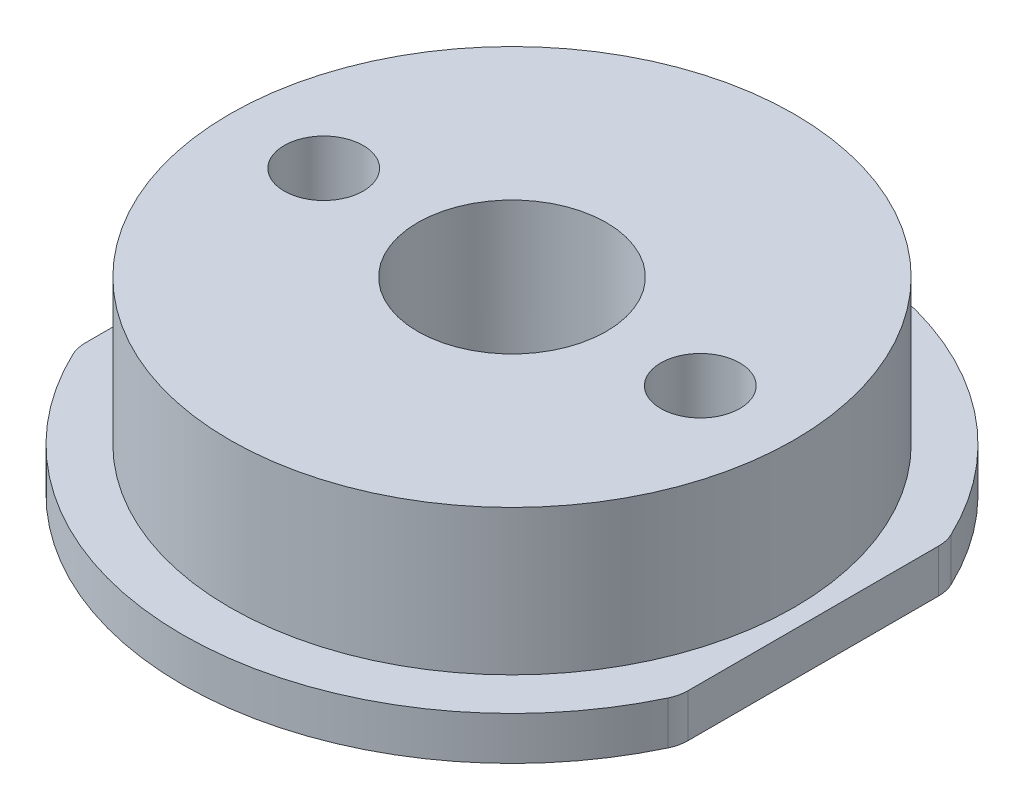
SolidWorks part; units mm, degrees
material "5052-H34"
ref_plane "正面" through (0, 0, 0) normal (0, 0, 1) x (1, 0, 0)
ref_plane "平面" through (0, 0, 0) normal (0, 1, 0) x (1, 0, 0)
ref_plane "右側面" through (0, 0, 0) normal (1, 0, 0) x (0, 0, -1)
sketch "ｽｹｯﾁ1" plane through (0, 0, 0) normal (0, 1, 0) x (1, 0, 0)
  circle A0 centre (0, 0) radius 17.5
  dimension "D1" = 35
extrude "ﾎﾞｽ - 押し出し1" add sketch "ｽｹｯﾁ1" along normal blind 2.3
sketch "ｽｹｯﾁ2" plane through (0, 2.3, 0) normal (0, 1, 0) x (1, 0, 0)
  circle A0 centre (0, 0) radius 14.99
  dimension "D1" = 29.98
extrude "ﾎﾞｽ - 押し出し2" add sketch "ｽｹｯﾁ2" along normal blind 7.7
sketch "ｽｹｯﾁ3" plane through (0, 0, 0) normal (0, -1, 0) x (1, 0, 0)
  line L0 (0, 17.5) -> (0, 0) construction
  line L1 (0, 0) -> (17.5, 0) construction
  line L15 (16, 7.0887) -> (16, -7.0887)
  line L16 (-16, 7.0887) -> (-16, -7.0887)
  circle A0 centre (0, 0) radius 5.01
  circle A1 centre (0, 0) radius 17.5 construction
  circle A2 centre (10, 0) radius 2.1
  circle A3 centre (-10, 0) radius 2.1
  arc A4 (16, -7.0887) -> (16, 7.0887) centre (0, 0) ccw
  arc A13 (-16, -7.0887) -> (-16, 7.0887) centre (0, 0) cw
  dimension "D1" = 10.02
  dimension "D2" = 4.2
  dimension "D3" = 20
  dimension "D4" = 32
extrude "ｶｯﾄ - 押し出し1" cut sketch "ｽｹｯﾁ3" against normal up to surface (10 mm away) up to face at (0, 10, 14.99)
fillet "ﾌｨﾚｯﾄ1" radius 2 4 edges at (-16, 1.15, -7.0887) (-16, 1.15, 7.0887) (16, 1.15, 7.0887) (16, 1.15, -7.0887)
